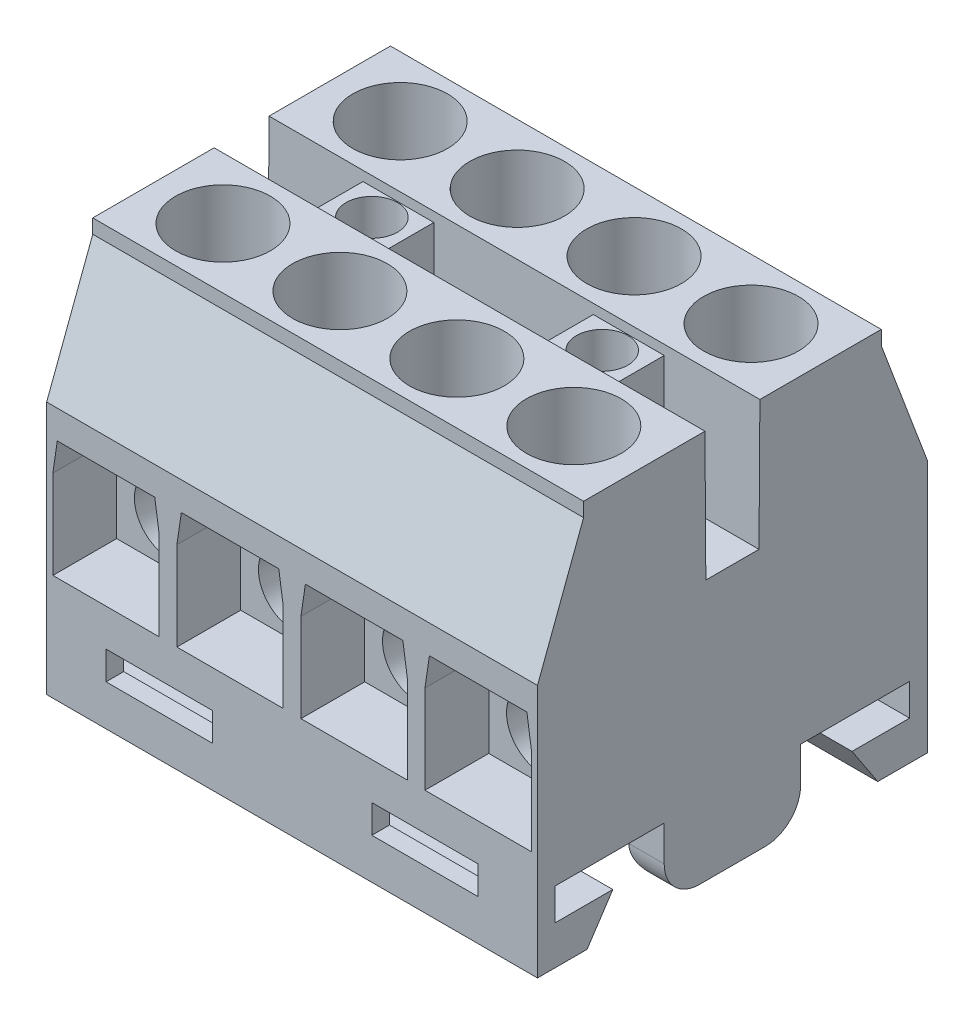
SolidWorks part; units mm, degrees
material "PE High Density"
ref_plane "Front" through (0, 0, 0) normal (0, 0, 1) x (1, 0, 0)
ref_plane "Top" through (0, 0, 0) normal (0, 1, 0) x (1, 0, 0)
ref_plane "Right" through (0, 0, 0) normal (1, 0, 0) x (0, 0, -1)
sketch "Sketch1" plane through (0, 0, 0) normal (0, 1, 0) x (1, 0, 0)
  line L1 (-13.85, 11) -> (13.85, 11)
  line L2 (-13.85, 11) -> (-13.85, -11)
  line L3 (-13.85, -11) -> (13.85, -11)
  line L4 (13.85, 11) -> (13.85, -11)
  line L5 (-13.85, 11) -> (13.85, -11) construction
  line L6 (-13.85, -11) -> (13.85, 11) construction
  point P0 (0, 0)
  dimension "D1" = 27.7
  dimension "D2" = 22
extrude "Boss-Extrude1" add sketch "Sketch1" along normal blind 22
sketch "Sketch2" plane through (13.85, 0, 0) normal (1, 0, 0) x (0, 0, -1)
  line L0 (-9.7, 17.75) -> (9.7, 17.75) construction
  line L1 (-11, 22) -> (-11, 0) construction
  line L2 (-8.4, 22) -> (-8.4, 21.2)
  line L3 (-8.4, 21.2) -> (-11, 14.3)
  line L4 (-11, 22) -> (11, 22) construction
  line L5 (-8.4, 22) -> (-11, 22)
  line L6 (-11, 22) -> (-11, 14.3)
  line L7 (-11, 0) -> (11, 0) construction
  line L8 (0, 0) -> (0, 22) construction
  line L9 (11, 22) -> (11, 14.3)
  line L10 (8.4, 22) -> (11, 22)
  line L11 (8.4, 22) -> (8.4, 21.2)
  line L12 (8.4, 21.2) -> (11, 14.3)
  dimension "D1" = 7.7
  dimension "D2" = 16.8
  dimension "D3" = 0.8
extrude "Cut-Extrude1" cut sketch "Sketch2" against normal through all
sketch "Sketch3" plane through (13.85, 0, 0) normal (1, 0, 0) x (0, 0, -1)
  line L0 (-8.4, 22) -> (8.4, 22) construction
  line L1 (-1.55, 22) -> (1.55, 22)
  line L2 (-1.55, 22) -> (-1.5, 14.7002)
  line L3 (-1.5, 14.7002) -> (1.5, 14.7002)
  line L4 (1.55, 22) -> (1.5, 14.7002)
  line L5 (0, 0) -> (0, 14.7002) construction
  line L6 (0, 14.7002) -> (0, 22) construction
  dimension "D1" = 3.1
  dimension "D2" = 7.3
  dimension "D3" = 3
extrude "Cut-Extrude2" cut sketch "Sketch3" against normal through all
sketch "Sketch4" plane through (13.85, 0, 0) normal (1, 0, 0) x (0, 0, -1)
  line L0 (-11, 0) -> (11, 0) construction
  line L1 (-6.75, 0) -> (6.75, 0)
  line L2 (-6.75, 0) -> (-6.75, 4)
  line L3 (-6.75, 4) -> (6.75, 4)
  line L4 (6.75, 0) -> (6.75, 4)
  line L5 (0, 0) -> (0, 4) construction
  dimension "D1" = 4
  dimension "D2" = 13.5
extrude "Cut-Extrude3" cut sketch "Sketch4" against normal through all
sketch "Sketch5" plane through (13.85, 0, 0) normal (1, 0, 0) x (0, 0, -1)
  line L0 (0, 0) -> (0, -1.4822) construction
  line L1 (-6.75, 4) -> (-10, 4)
  line L2 (-6.75, 4) -> (-6.75, 2.2)
  line L3 (-6.75, 2.2) -> (-10, 2.2)
  line L4 (-10, 4) -> (-10, 2.2)
  line L5 (10, 4) -> (10, 2.2)
  line L6 (6.75, 2.2) -> (10, 2.2)
  line L7 (6.75, 4) -> (6.75, 2.2)
  line L8 (6.75, 4) -> (10, 4)
  dimension "D1" = 10
  dimension "D2" = 1.8
extrude "Cut-Extrude4" cut sketch "Sketch5" against normal through all
sketch "Sketch6" plane through (13.85, 0, 0) normal (1, 0, 0) x (0, 0, -1)
  line L0 (-8.2, 0) -> (-6.75, 2.2)
  line L1 (-11, 0) -> (-6.75, 0) construction
  line L2 (-6.75, 2.2) -> (-6.75, 0)
  line L3 (-6.75, 0) -> (-8.2, 0)
  line L4 (10, 4) -> (-10, 4) construction
  line L5 (0, 0) -> (0, 4) construction
  line L6 (6.75, 0) -> (8.2, 0)
  line L7 (6.75, 2.2) -> (6.75, 0)
  line L8 (8.2, 0) -> (6.75, 2.2)
  dimension "D1" = 16.4
extrude "Cut-Extrude5" cut sketch "Sketch6" against normal through all
sketch "Sketch7" plane through (0, 0, 11) normal (0, 0, 1) x (1, 0, 0)
  line L1 (-4.5, 3.9) -> (4.5, 3.9) construction
  line L2 (-4.5, 3.9) -> (-4.5, 2.3) construction
  line L3 (-4.5, 2.3) -> (4.5, 2.3) construction
  line L4 (4.5, 3.9) -> (4.5, 2.3) construction
  line L5 (-4.5, 3.9) -> (4.5, 2.3) construction
  line L6 (-4.5, 2.3) -> (4.5, 3.9) construction
  line L7 (-4.5, 2.3) -> (-10.5, 2.3)
  line L8 (-4.5, 2.3) -> (-4.5, 3.9)
  line L9 (-4.5, 3.9) -> (-10.5, 3.9)
  line L10 (-10.5, 2.3) -> (-10.5, 3.9)
  line L11 (4.5, 2.3) -> (10.5, 2.3)
  line L12 (4.5, 2.3) -> (4.5, 3.9)
  line L13 (4.5, 3.9) -> (10.5, 3.9)
  line L14 (10.5, 2.3) -> (10.5, 3.9)
  point P0 (0, 3.1)
  point P12 (-10.5, 3.1)
  dimension "D1" = 1.6
  dimension "D2" = 2.3
  dimension "D3" = 9
  dimension "D4" = 6
extrude "Cut-Extrude6" cut sketch "Sketch7" against normal through all
sketch "Sketch8" plane through (0, 22, 0) normal (0, 1, 0) x (1, 0, 0)
  line L0 (-9.9, 5) -> (-3.3, 5) construction
  line L1 (-3.3, 5) -> (3.3, 5) construction
  line L2 (3.3, 5) -> (9.9, 5) construction
  line L3 (9.9, 5) -> (9.9, -5) construction
  circle A0 centre (-9.9, 5) radius 2.675
  circle A1 centre (-3.3, 5) radius 2.675
  circle A2 centre (3.3, 5) radius 2.675
  circle A3 centre (9.9, 5) radius 2.675
  circle A4 centre (9.9, -5) radius 2.675
  circle A5 centre (3.3, -5) radius 2.675
  circle A6 centre (-3.3, -5) radius 2.675
  circle A7 centre (-9.9, -5) radius 2.675
  point P18 (0, 0)
  point P19 (0, 5)
  point P23 (9.9, 0)
  dimension "D2" = 5.35
  dimension "D3" = 6.6
  dimension "D1" = 10
extrude "Cut-Extrude7" cut sketch "Sketch8" against normal blind 4.5
sketch "Sketch9" plane through (0, 0, 11) normal (0, 0, 1) x (1, 0, 0)
  line L1 (-13.85, 14.3) -> (13.85, 14.3) construction
  line L2 (-13.5, 11) -> (-13.25, 12.7)
  line L3 (-13.5, 11) -> (-7.5, 11) construction
  line L4 (-13.5, 11) -> (-13.5, 6)
  line L7 (-13.5, 6) -> (-7.5, 6)
  line L8 (-7.5, 11) -> (-7.5, 6)
  line L9 (-6.5, 11) -> (-0.5, 11) construction
  line L10 (-6.5, 11) -> (-6.5, 6)
  line L11 (-6.5, 6) -> (-0.5, 6)
  line L12 (-0.5, 11) -> (-0.5, 6)
  line L13 (0, 0) -> (0, 14.3) construction
  line L14 (-13.85, 0) -> (13.85, 0) construction
  line L15 (0.5, 11) -> (6.5, 11) construction
  line L16 (0.5, 11) -> (0.5, 6)
  line L17 (0.5, 6) -> (6.5, 6)
  line L18 (6.5, 11) -> (6.5, 6)
  line L19 (7.5, 11) -> (13.5, 11) construction
  line L20 (7.5, 11) -> (7.5, 6)
  line L21 (7.5, 6) -> (13.5, 6)
  line L22 (13.5, 11) -> (13.5, 6)
  line L23 (-13.25, 12.7) -> (-7.75, 12.7)
  line L24 (-7.75, 12.7) -> (-7.5, 11)
  line L25 (-6.5, 11) -> (-6.25, 12.7)
  line L26 (-6.25, 12.7) -> (-0.75, 12.7)
  line L27 (-0.75, 12.7) -> (-0.5, 11)
  line L28 (0.5, 11) -> (0.75, 12.7)
  line L29 (0.75, 12.7) -> (6.25, 12.7)
  line L30 (6.25, 12.7) -> (6.5, 11)
  line L31 (7.5, 11) -> (7.75, 12.7)
  line L32 (7.75, 12.7) -> (13.25, 12.7)
  line L33 (13.25, 12.7) -> (13.5, 11)
  line L34 (-7.5, 6) -> (-6.5, 6)
  line L35 (-0.5, 6) -> (0.5, 6)
  line L36 (6.5, 6) -> (7.5, 6)
  point P25 (-10.5, 12.7)
  point P32 (-10.5, 6)
  point P33 (0, 6)
  dimension "D1" = 1
  dimension "D2" = 6
  dimension "D3" = 5
  dimension "D4" = 6.7
  dimension "D5" = 5.5
  dimension "D6" = 6
extrude "Cut-Extrude8" cut sketch "Sketch9" against normal blind 3.6 contours L24 L23 L2 L4 L7 L8 | L27 L26 L25 L10 L11 L12 | L30 L29 L28 L16 L17 L18 | L33 L32 L31 L20 L21 L22
mirror "Mirror1" about plane through (0, 0, 0) normal (0, 0, 1) of "Cut-Extrude8"
sketch "Sketch10" plane through (0, 0, 7.4) normal (0, 0, 1) x (1, 0, 0)
  line L0 (-13.5, 6) -> (-7.5, 6) construction
  line L4 (-6.5, 6) -> (-0.5, 6) construction
  line L7 (0.5, 6) -> (6.5, 6) construction
  line L8 (7.5, 6) -> (13.5, 6) construction
  line L9 (-13.5, 11) -> (-13.5, 6) construction
  line L10 (-13.5, 11) -> (-13.5, 6) construction
  circle A0 centre (-10.5, 8.5) radius 2
  circle A1 centre (-3.5, 8.5) radius 2
  circle A2 centre (3.5, 8.5) radius 2
  circle A3 centre (10.5, 8.5) radius 2
  point P8 (-10.5, 6)
  point P9 (-3.5, 6)
  point P12 (3.5, 6)
  point P16 (10.5, 6)
  point P23 (-13.5, 8.5)
  dimension "D1" = 4
extrude "Cut-Extrude9" cut sketch "Sketch10" against normal blind 3
mirror "Mirror2" about plane through (0, 0, 0) normal (0, 0, 1) of "Cut-Extrude9"
sketch "Sketch15" plane through (0, 14.7002, 0) normal (0, 1, 0) x (1, 0, 0)
  line L11 (-13.85, -1.55) -> (13.85, -1.55) construction
  line L12 (-13.85, 1.55) -> (13.85, 1.55) construction
  line L13 (-13.85, -1.55) -> (13.85, -1.55) construction
  line L14 (-13.85, 1.55) -> (13.85, 1.55) construction
  line L15 (13.85, 0) -> (0, 0) construction
  line L16 (13.85, -1.5) -> (13.85, 1.5) construction
  line L17 (8.5, 0) -> (4.5, 0) construction
  line L18 (-8.5, 1.55) -> (-4.5, 1.55)
  line L19 (-8.5, 1.55) -> (-8.5, -1.55)
  line L20 (-8.5, -1.55) -> (-4.5, -1.55)
  line L21 (-4.5, 1.55) -> (-4.5, -1.55)
  line L22 (4.5, 1.55) -> (8.5, 1.55)
  line L23 (4.5, 1.55) -> (4.5, -1.55)
  line L24 (4.5, -1.55) -> (8.5, -1.55)
  line L25 (8.5, 1.55) -> (8.5, -1.55)
  line L26 (6.5, 0) -> (-6.5, 0) construction
  circle A2 centre (6.5, 0) radius 1.45
  circle A3 centre (-6.5, 0) radius 1.45
  point P23 (0, 0)
  point P24 (6.5, 0)
  point P25 (-6.5, 1.55)
  line M15 (13.85, 1.5) -> (-13.85, 1.5)
  line M17 (-13.85, -1.5) -> (13.85, -1.5)
  dimension "D1" = 2.9
  dimension "D2" = 4
  dimension "D3" = 13
extrude "Boss-Extrude4" add sketch "Sketch15" along normal blind 6.8 contours L21 L19 A3 M15 M17 | L25 L23 A2 M15 M17
sketch "Sketch11" plane through (0, 4, 0) normal (0, -1, 0) x (1, 0, 0)
  line L0 (13.85, -10) -> (13.85, 10) construction
  line L1 (11.85, 3.85) -> (22.35, 3.85)
  line L2 (11.85, 3.85) -> (11.85, -3.85)
  line L3 (11.85, -3.85) -> (22.35, -3.85)
  line L4 (22.35, 3.85) -> (22.35, -3.85)
  line L5 (11.85, 3.85) -> (22.35, -3.85) construction
  line L6 (11.85, -3.85) -> (22.35, 3.85) construction
  point P0 (17.1, 0)
  dimension "D1" = 2
  dimension "D2" = 10.5
  dimension "D3" = 7.7
extrude "Boss-Extrude2" add sketch "Sketch11" along normal up to surface (4 mm away) up to face at (0, 0, 9.6)
sketch "Sketch12" plane through (0, 4, 0) normal (0, 1, 0) x (1, 0, 0)
  line L1 (22.35, 3.85) -> (22.35, -3.85) construction
  line L2 (22.35, 3.85) -> (22.35, -3.85) construction
  circle A0 centre (18.35, 0) radius 3
  dimension "D2" = 6
  dimension "D1" = 4
extrude "Cut-Extrude10" cut sketch "Sketch12" against normal blind 3.5
sketch "Sketch13" plane through (0, 0.5, 0) normal (0, 1, 0) x (1, 0, 0)
  circle A0 centre (18.35, 0) radius 1.5
  circle A1 centre (18.35, 0) radius 3 construction
  dimension "D1" = 3
extrude "Reikä. Mahtuu 3,3mm niitti läpi, koska materiaali muovia" cut sketch "Sketch13" against normal through all
sketch "Sketch14" plane through (0, 0, 0) normal (0, -1, 0) x (1, 0, 0)
  line L0 (-13.85, 8.2) -> (-14.35, 8.2)
  line L1 (-13.85, 10.1) -> (-16.35, 10.1)
  line L2 (-13.85, 8.2) -> (-13.85, 11) construction
  line L3 (-13.85, 10.1) -> (-13.85, 8.2)
  line L4 (0, 0) -> (11.85, 0) construction
  line L5 (-13.85, -10.1) -> (-13.85, -8.2)
  line L6 (-13.85, -10.1) -> (-16.35, -10.1)
  line L7 (-13.85, -8.2) -> (-14.35, -8.2)
  line L8 (11.85, -3.85) -> (11.85, 3.85) construction
  line L10 (-13.85, 8.2) -> (-11.95, 8.2)
  line L11 (-13.85, 8.2) -> (-13.85, 10.1)
  line L12 (-13.85, 10.1) -> (-11.95, 10.1)
  line L13 (-11.95, 8.2) -> (-11.95, 10.1)
  arc A0 (-16.35, 10.1) -> (-14.35, 8.2) centre (-14.35, 10.2026) ccw
  arc A1 (-16.35, -10.1) -> (-14.35, -8.2) centre (-14.35, -10.2026) cw
  dimension "D1" = 2.5
  dimension "D2" = 2
  dimension "D3" = 1.9
extrude "Boss-Extrude3" [suppressed] add sketch "Sketch14" against normal blind 5 contours L10 L13 L12 L3 | L1 A0 L0 L3
fillet "Fillet2" radius 2 4 edges at (22.35, 0, 0) (17.1, 0, -3.85) (17.1, 0, 3.85) (11.85, 0, 0)
fillet "Fillet3" radius 1 4 edges at (21.7642, 0.5858, 3.2642) (21.7642, 0.5858, -3.2642) (22.35, 3, 3.85) (22.35, 3, -3.85)
ref_plane "Plane1" through (0, 0, 0) normal (0, 0, 1) x (1, 0, 0)
sketch "Sketch16" plane through (0, 0, 0) normal (0, 0, 1) x (1, 0, 0)
  line L0 (11.85, 2) -> (11.85, 4) construction
  line L1 (11.85, 2) -> (11.85, 4)
  line L2 (-13.85, 4) -> (13.85, 4) construction
  line L3 (9.85, 4) -> (11.85, 4)
  line L4 (11.85, 2) -> (9.85, 4)
  dimension "D1" = 45
extrude "Boss-Extrude5" add sketch "Sketch16" along normal mid plane 2.3
sketch "Sketch17" [suppressed] plane through (0, 0, 0) normal (0, -1, 0) x (1, 0, 0)
  line L0 (-11.95, 10) -> (13.85, 10) construction
  line L1 (-13.85, -10) -> (13.85, -10) construction
  line L2 (-11.95, 10) -> (13.85, 10) construction
  line L3 (-13.85, -10) -> (13.85, -10) construction
  line L4 (0, 0) -> (6.68, 0) construction
  line L5 (-13.85, 6.75) -> (13.85, 6.75) construction
  line L6 (13.85, 10) -> (9.85, 10)
  line L7 (13.85, 10) -> (13.85, 6.75)
  line L8 (13.85, 6.75) -> (9.85, 6.75)
  line L9 (9.85, 10) -> (9.85, 6.75)
  line L10 (4.85, 10) -> (-4.75, 10)
  line L11 (4.85, 10) -> (4.85, 6.75)
  line L12 (4.85, 6.75) -> (-4.75, 6.75)
  line L13 (-4.75, 10) -> (-4.75, 6.75)
  line L14 (-9.75, 6.75) -> (-12.25, 6.75)
  line L15 (-9.75, 6.75) -> (-9.75, 9.5)
  line L16 (-9.75, 9.5) -> (-12.25, 9.5)
  line L17 (-12.25, 6.75) -> (-12.25, 9.5)
  line L18 (-13.85, 8.2) -> (-12.25, 8.2)
  line L19 (-13.85, 8.2) -> (-13.85, 6.75)
  line L20 (-13.85, 6.75) -> (-12.25, 6.75)
  line L22 (-13.85, 6.75) -> (13.85, 6.75) construction
  line L23 (-13.85, 11) -> (13.85, 11) construction
  line L24 (-13.85, 8.2) -> (13.85, 8.2) construction
  dimension "D1" = 4
  dimension "D2" = 5
  dimension "D3" = 9.6
  dimension "D4" = 5
  dimension "D5" = 1.5
  dimension "D6" = 2.5
extrude "Cut-Extrude11" [suppressed] cut sketch "Sketch17" against normal up to surface (4 mm away) contours L17 L14 L15 L16 | L19 L20 L17 L18 | L10 L13 L12 L11 | L6 L9 L8 L7
mirror "Mirror3" [suppressed] about plane through (0, 0, 0) normal (0, 0, 1)
sketch "Sketch18" plane through (0, 4, 0) normal (0, -1, 0) x (1, 0, 0)
  line L0 (-13.85, 10) -> (13.85, 10) construction
  line L1 (1.85, 10) -> (2.85, 10)
  line L2 (1.85, 10) -> (1.85, 8.2)
  line L3 (1.85, 8.2) -> (2.85, 8.2)
  line L4 (2.85, 10) -> (2.85, 8.2)
  line L5 (-13.85, -10) -> (13.85, -10) construction
  line L6 (1.85, -10) -> (2.85, -10)
  line L7 (1.85, -10) -> (1.85, -8.2)
  line L8 (1.85, -8.2) -> (2.85, -8.2)
  line L9 (2.85, -10) -> (2.85, -8.2)
  line L10 (-13.85, 8.2) -> (13.85, 8.2) construction
  line L11 (13.85, 3.85) -> (13.85, 10) construction
  dimension "D1" = 1
  dimension "D2" = 12
extrude "Boss-Extrude6" add sketch "Sketch18" along normal up to surface (4 mm away)
sketch "Sketch19" plane through (0, 0, 3.85) normal (0, 0, 1) x (1, 0, 0)
  line L0 (22.35, 4) -> (22.35, 2) construction
  line L1 (13.85, 4) -> (22.35, 4)
  line L2 (13.85, 4) -> (13.85, 0)
  line L3 (13.85, 0) -> (22.35, 0)
  line L4 (22.35, 4) -> (22.35, 0)
  line L5 (20.35, 0) -> (13.85, 0) construction
extrude "Cut-Extrude12" cut sketch "Sketch19" against normal through all
equation "\"D1@Sketch12\"=\"D2@Sketch12\"/2+1"
